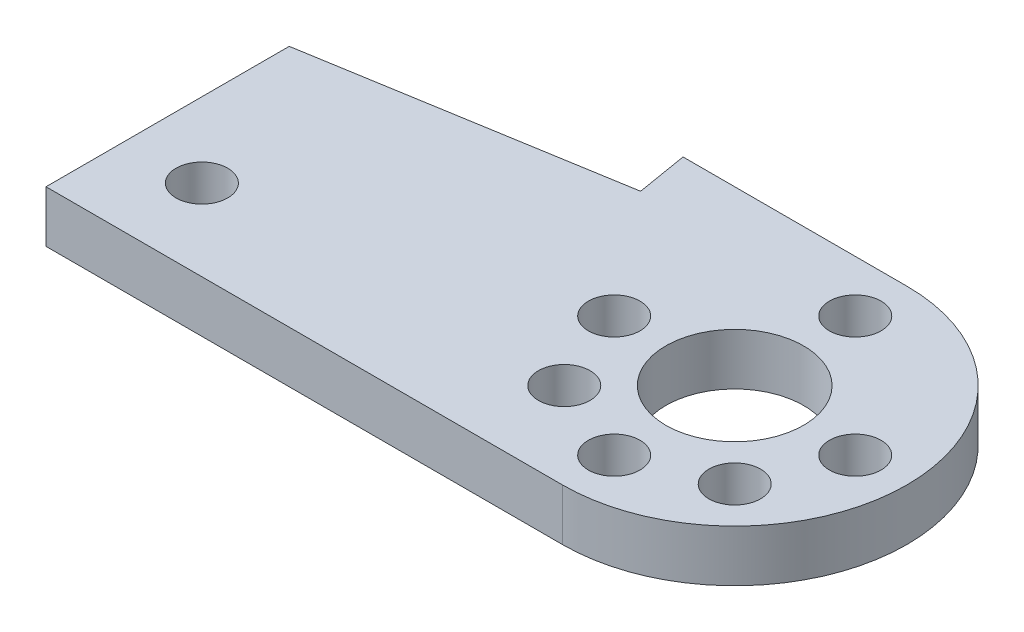
SolidWorks part; units mm, degrees
ref_plane "前视基准面" through (0, 0, 0) normal (0, 0, 1) x (1, 0, 0)
ref_plane "上视基准面" through (0, 0, 0) normal (0, 1, 0) x (1, 0, 0)
ref_plane "右视基准面" through (0, 0, 0) normal (1, 0, 0) x (0, 0, -1)
other "Configuration Table"
sketch "草图1" plane through (0, 0, 0) normal (0, 1, 0) x (1, 0, 0)
  circle A0 centre (0, 0) radius 10
extrude "凸台-拉伸1" add sketch "草图1" along normal blind 3
sketch "草图2" plane through (0, 3, 0) normal (0, 1, 0) x (1, 0, 0)
  circle A0 centre (0, 0) radius 4
extrude "切除-拉伸1" cut sketch "草图2" against normal through all
sketch "草图3" plane through (0, 3, 0) normal (0, 1, 0) x (1, 0, 0)
  line L0 (7, 0) -> (-7, 0) construction
  line L1 (0, 0) -> (7, 0) construction
  line L2 (0, 0) -> (4.9497, -4.9497) construction
  line L3 (0, 7) -> (0, -7) construction
  circle A0 centre (7, 0) radius 1.5
  circle A1 centre (4.9497, -4.9497) radius 1.5
  circle A2 centre (0, -7) radius 1.5
  circle A3 centre (-4.9497, -4.9497) radius 1.5
  circle A4 centre (-7, 0) radius 1.5
  circle A5 centre (0, 7) radius 1.5
  point P4 (0, 0)
  point P20 (0, 0)
  dimension "D2" = 5
  dimension "D1" = 14
  dimension "D3" = 45
extrude "切除-拉伸2" cut sketch "草图3" against normal through all
sketch "草图6" plane through (0, 3, 0) normal (0, 1, 0) x (1, 0, 0)
  line L0 (0, 10) -> (-30, 10)
  line L1 (0, -10) -> (-30, -10)
  line L2 (-30, 10) -> (-30, -10)
  circle A0 centre (0, 0) radius 10 construction
  arc A1 (0, 10) -> (0, -10) centre (0, 0) ccw
  point P7 (0, 0)
  point P9 (0, 0)
  dimension "D1" = 30
extrude "凸台-拉伸3" add sketch "草图6" against normal blind 3
sketch "草图7" plane through (0, 3, 0) normal (0, 1, 0) x (1, 0, 0)
  line L0 (-30, 4.1253) -> (-12.5068, 7.0408)
  line L1 (-30, 10) -> (-30, -10) construction
  line L2 (-12.5068, 7.0408) -> (-140.738, -14.331) construction
  line L3 (-12.5068, 7.0408) -> (-13, 10)
  line L4 (0, 10) -> (-30, 10) construction
  line L5 (-12.5068, 7.0408) -> (-13, 10) construction
  line L6 (-13, 10) -> (-30, 10)
  line L7 (-30, 10) -> (-30, 4.1253)
extrude "切除-拉伸3" cut sketch "草图7" against normal through all
sketch "草图10" plane through (0, 0, 0) normal (0, -1, 0) x (1, 0, 0)
  circle A0 centre (-25.6587, 5.2891) radius 1.5
extrude "切除-拉伸6" cut sketch "草图10" against normal through all
